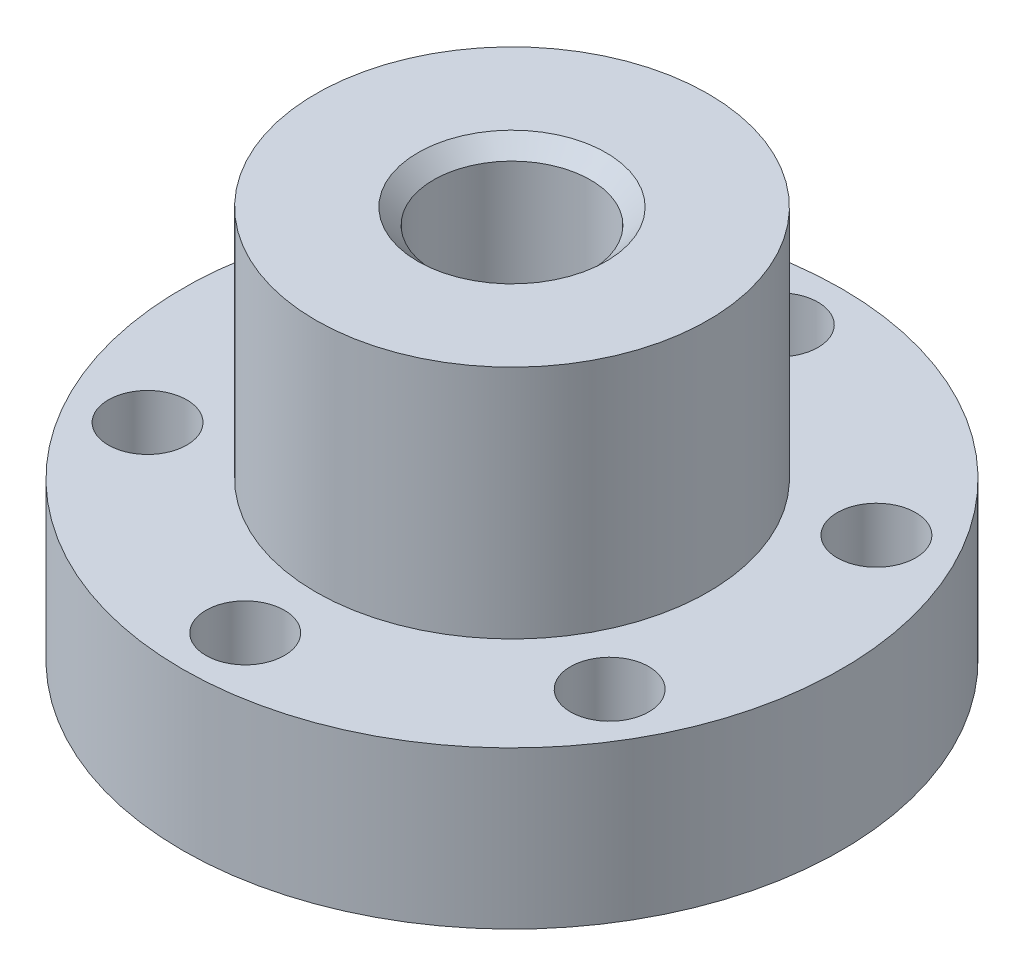
SolidWorks part; units mm, degrees
ref_plane "Front Plane" through (0, 0, 0) normal (0, 0, 1) x (1, 0, 0)
ref_plane "Top Plane" through (0, 0, 0) normal (0, 1, 0) x (1, 0, 0)
ref_plane "Right Plane" through (0, 0, 0) normal (1, 0, 0) x (0, 0, -1)
sketch "Sketch1" plane through (0, 0, 0) normal (0, 1, 0) x (1, 0, 0)
  circle A0 centre (0, 0) radius 21
  circle A1 centre (0, 17) radius 2.5
  circle A2 centre (14.7224, 8.5) radius 2.5
  circle A3 centre (14.7224, -8.5) radius 2.5
  circle A4 centre (0, -17) radius 2.5
  circle A5 centre (-14.7224, -8.5) radius 2.5
  circle A6 centre (-14.7224, 8.5) radius 2.5
  point P17 (0, 0)
  dimension "D1" = 42
  dimension "D2" = 5
  dimension "D3" = 17
  dimension "D5" = 17
  dimension "D4" = 6
extrude "Boss-Extrude1" add sketch "Sketch1" along normal blind 10
sketch "Sketch2" plane through (0, 10, 0) normal (0, 1, 0) x (1, 0, 0)
  circle A0 centre (0, 0) radius 12.5
  dimension "D1" = 25
extrude "Boss-Extrude2" add sketch "Sketch2" along normal blind 15
sketch "Sketch3" plane through (0, 25, 0) normal (0, 1, 0) x (1, 0, 0)
  circle A0 centre (0, 0) radius 5
  dimension "D1" = 10
extrude "Cut-Extrude1" cut sketch "Sketch3" against normal through all
chamfer "Chamfer1" distance 1 angle 45 2 edges at (0, 0, 5) (0, 25, 5)
